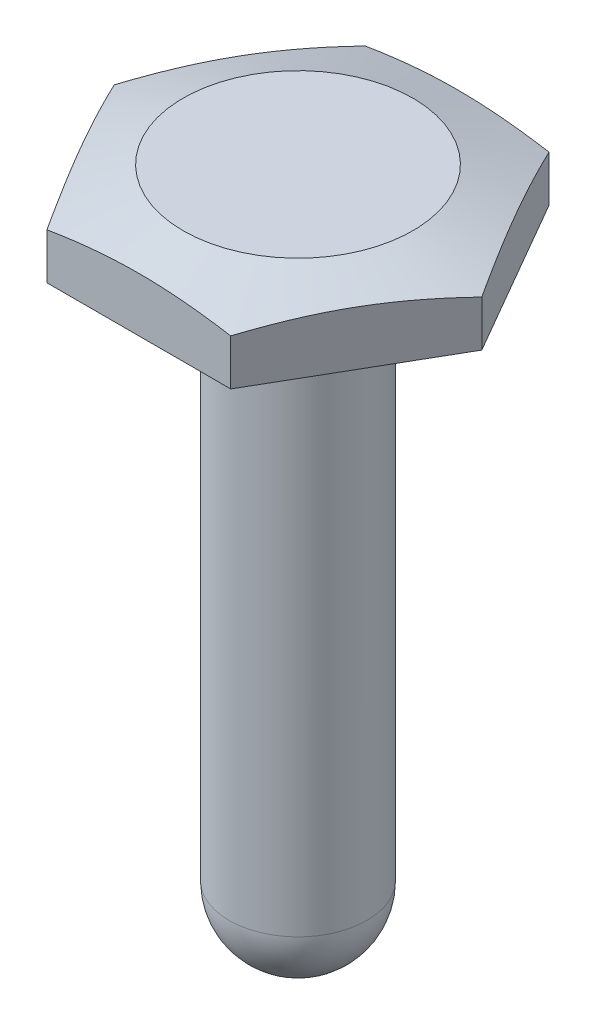
SolidWorks part; units mm, degrees
material "2.1020 (CuSn6)"
ref_plane "Front Plane" through (0, 0, 0) normal (0, 0, 1) x (1, 0, 0)
ref_plane "Top Plane" through (0, 0, 0) normal (0, 1, 0) x (1, 0, 0)
ref_plane "Right Plane" through (0, 0, 0) normal (1, 0, 0) x (0, 0, -1)
sketch "Sketch1" plane through (0, 0, 0) normal (0, 0, 1) x (1, 0, 0)
  line L0 (0, 0) -> (0, -95.25)
  line L1 (0, -55) -> (0, 55) construction
  line L3 (9.525, -85.725) -> (9.525, -9.525)
  line L4 (9.525, -9.525) -> (25.4, -9.525)
  line L5 (25.4, -9.525) -> (25.4, -3.175)
  line L6 (25.4, -3.175) -> (15.875, 0)
  line L7 (55, 0) -> (-55, 0) construction
  line L8 (15.875, 0) -> (0, 0)
  arc A0 (0, -95.25) -> (9.525, -85.725) centre (0, -85.725) ccw
  point P14 (0, 0)
  dimension "D6" = 9.525
  dimension "D1" = 95.25
  dimension "D2" = 9.525
  dimension "D3" = 6.35
  dimension "D4" = 9.525
  dimension "D5" = 15.875
  dimension "D7" = 9.525
revolve "Pin Base" add sketch "Sketch1" angle 360 about L0
sketch "Sketch2" plane through (0, 0, 0) normal (0, 1, 0) x (1, 0, 0)
  line L1 (25.4, 0) -> (12.7, 21.997)
  line L2 (12.7, 21.997) -> (-12.7, 21.997)
  line L3 (-12.7, 21.997) -> (-25.4, 0)
  line L4 (-25.4, 0) -> (-12.7, -21.997)
  line L5 (-12.7, -21.997) -> (12.7, -21.997)
  line L6 (12.7, -21.997) -> (25.4, 0)
  circle A0 centre (0, 0) radius 21.997 construction
  circle A1 centre (0, 0) radius 25.4 construction
  point P1 (12.6996, -21.9973)
extrude "Hex Cut" cut sketch "Sketch2" against normal through all flip side to cut
